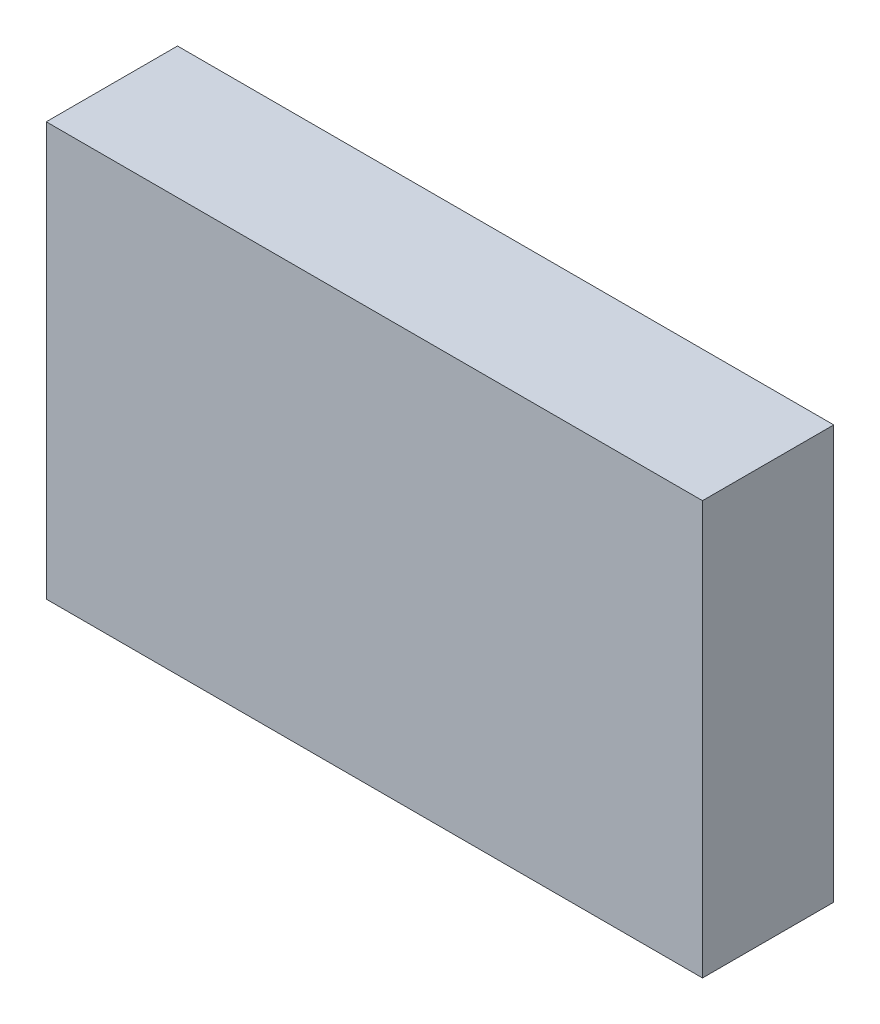
SolidWorks part; units mm, degrees
ref_plane "Front Plane" through (0, 0, 0) normal (0, 0, 1) x (1, 0, 0)
ref_plane "Top Plane" through (0, 0, 0) normal (0, 1, 0) x (1, 0, 0)
ref_plane "Right Plane" through (0, 0, 0) normal (1, 0, 0) x (0, 0, -1)
sketch "Sketch1" plane through (0, 0, 0) normal (0, 1, 0) x (1, 0, 0)
  line L1 (-3.1663, 1.1656) -> (9.5337, 1.1656)
  line L2 (-3.1663, 1.1656) -> (-3.1663, -1.3744)
  line L3 (-3.1663, -1.3744) -> (9.5337, -1.3744)
  line L4 (9.5337, 1.1656) -> (9.5337, -1.3744)
  dimension "D1" = 2.54
  dimension "D2" = 12.7
extrude "Boss-Extrude1" add sketch "Sketch1" along normal blind 8
